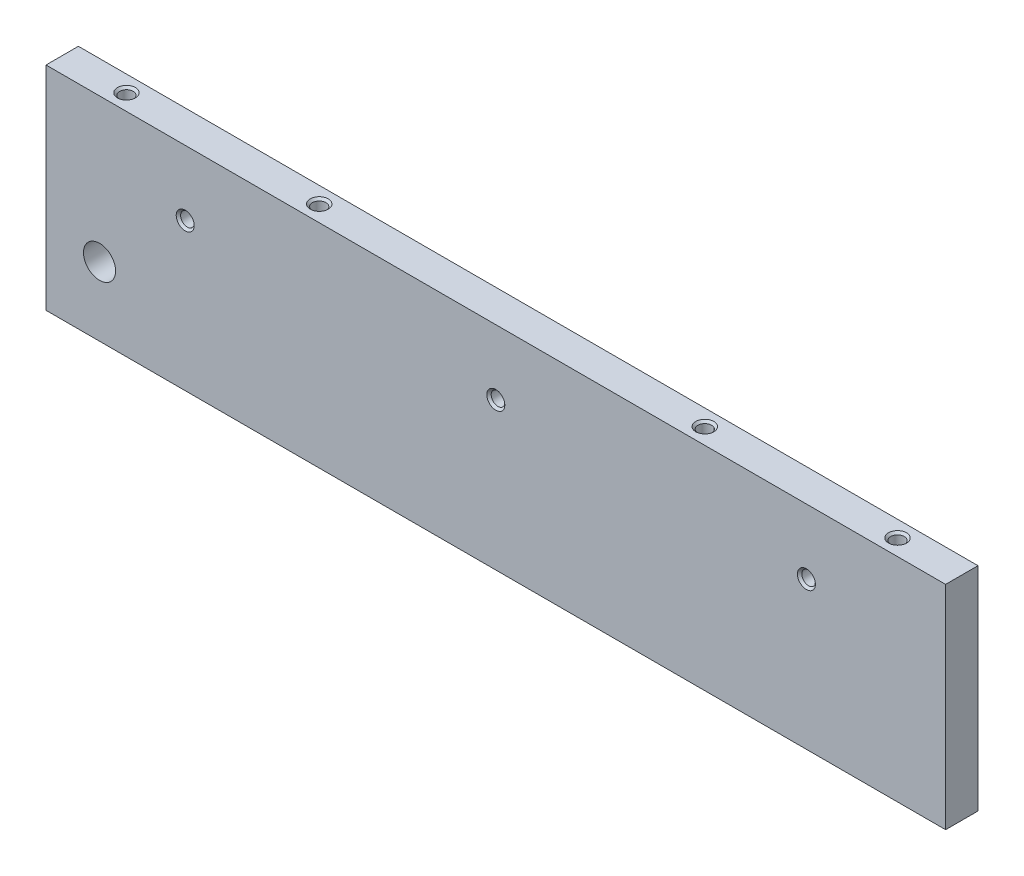
SolidWorks part; units mm, degrees
ref_plane "Front Plane" through (0, 0, 0) normal (0, 0, 1) x (1, 0, 0)
ref_plane "Top Plane" through (0, 0, 0) normal (0, 1, 0) x (1, 0, 0)
ref_plane "Right Plane" through (0, 0, 0) normal (1, 0, 0) x (0, 0, -1)
sketch "Sketch1" plane through (0, 0, 0) normal (0, 0, 1) x (1, 0, 0)
  line L1 (-133.35, 0) -> (133.35, 0)
  line L2 (-133.35, 0) -> (-133.35, -62.992)
  line L3 (-133.35, -62.992) -> (133.35, -62.992)
  line L4 (133.35, 0) -> (133.35, -62.992)
  dimension "D1" = 62.992
  dimension "D2" = 266.7
extrude "Boss-Extrude1" add sketch "Sketch1" along normal blind 9.6012
hole_wizard "#10-32 Tapped Hole1" positions "Sketch3" profile "Sketch2" tap size "#10-32" standard "ANSI Inch" end condition up to next
sketch "Sketch3" plane through (0, 0, 9.6012) normal (0, 0, 1) x (1, 0, 0)
  point P0 (92.075, -19.304)
  point P2 (0, -19.304)
  point P4 (-92.075, -19.304)
  dimension "D1" = 92.075
  dimension "D2" = 92.075
  dimension "D3" = 19.304
sketch "Sketch2" plane through (92.075, -19.304, 9.6012) normal (1, 0, 0) x (0, -1, 0)
  line L0 (0, 0) -> (0, 9.6012)
  line L1 (0, 9.6012) -> (2.667, 9.6012)
  line L2 (2.0193, 8.9535) -> (2.0193, 0.6477)
  line L3 (2.0193, 0.6477) -> (2.667, 0)
  line L5 (2.667, 0) -> (0, 0)
  line L6 (-2.0193, 0.6477) -> (-2.667, 0) construction
  line L7 (2.667, 9.6012) -> (2.0193, 8.9535)
  line L8 (-2.667, 9.6012) -> (-2.0193, 8.9535) construction
  line L11 (0, -6.35) -> (0, 107.95) construction
  dimension "Thread Major Dia." = 4.0386
  dimension "Thru Tap Drill Depth" = 9.6012
  dimension "Near C'Sink Dia." = 5.334
  dimension "Near C'Sink Angle" = 90
  dimension "Far C'Sink Dia." = 5.334
  dimension "Far C'Sink Angle" = 90
hole_wizard "3/8 (0.3750) Dowel Hole1" positions "Sketch5" profile "Sketch4" hole size "3/8" standard "ANSI Inch" end condition up to next
sketch "Sketch5" plane through (0, 0, 9.6012) normal (0, 0, 1) x (1, 0, 0)
  point P0 (-117.475, -42.5958)
  dimension "D1" = 42.5958
  dimension "D2" = 117.475
sketch "Sketch4" plane through (-117.475, -42.5958, 9.6012) normal (1, 0, 0) x (0, -1, 0)
  line L0 (0, 0) -> (0, 9.6012)
  line L1 (0, 9.6012) -> (4.7625, 9.6012)
  line L2 (4.7625, 9.6012) -> (4.7625, 0)
  line L5 (4.7625, 0) -> (0, 0)
  line L11 (0, -6.35) -> (0, 107.95) construction
  dimension "Thru Hole Dia." = 9.525
  dimension "Thru Hole Depth" = 9.6012
hole_wizard "#10-32 Tapped Hole2" positions "Sketch14" profile "Sketch13" tap size "#10-32" standard "ANSI Inch"
sketch "Sketch14" plane through (0, 0, 0) normal (0, 1, 0) x (1, 0, 0)
  point P0 (114.3, -4.8006)
  point P2 (57.15, -4.8006)
  point P4 (-57.15, -4.8006)
  point P6 (-114.3, -4.8006)
  dimension "D1" = 4.8006
  dimension "D2" = 57.15
  dimension "D3" = 57.15
  dimension "D4" = 57.15
  dimension "D5" = 57.15
sketch "Sketch13" plane through (114.3, 0, 4.8006) normal (1, 0, 0) x (0, 0, 1)
  line L0 (0, 0) -> (0, 20.2633)
  line L1 (0, 20.2633) -> (2.0193, 19.05)
  line L2 (2.0193, 19.05) -> (2.0193, 0.6477)
  line L3 (2.0193, 0.6477) -> (2.667, 0)
  line L5 (2.667, 0) -> (0, 0)
  line L6 (-2.0193, 0.6477) -> (-2.667, 0) construction
  line L10 (0, 20.2633) -> (-2.0193, 19.05) construction
  line L11 (0, -6.35) -> (0, 107.95) construction
  dimension "Tap Drill Dia." = 4.0386
  dimension "Tap Drill Depth" = 19.05
  dimension "Near C'Sink Dia." = 5.334
  dimension "Near C'Sink Angle" = 90
  dimension "Drill Angle" = 118
sketch "Sketch6" plane through (0, 0, 0) normal (0, 1, 0) x (1, 0, 0)
  line L1 (-133.35, 222.25) -> (133.35, 222.25)
  line L2 (-133.35, 222.25) -> (-133.35, -14.3002)
  line L3 (-133.35, -14.3002) -> (133.35, -14.3002)
  line L4 (133.35, 222.25) -> (133.35, -14.3002)
  point P4 (0, 222.25)
  dimension "D1" = 14.3002
  dimension "D2" = 266.7
  dimension "D3" = 222.25
extrude "Boss-Extrude2" [suppressed] add sketch "Sketch6" along normal blind 6.35 separate body
hole_wizard "1/2 (0.5000) Dowel Hole1" [suppressed] positions "Sketch8" profile "Sketch7" hole size "1/2" standard "ANSI Inch"
sketch "Sketch8" [suppressed] plane through (0, 6.35, 0) normal (0, 1, 0) x (1, 0, 0)
  point P0 (114.3, 201.6252)
  point P2 (-114.3, 201.6252)
  dimension "D1" = 201.6252
  dimension "D2" = 114.3
  dimension "D3" = 114.3
sketch "Sketch7" plane through (114.3, 6.35, -201.6252) normal (1, 0, 0) x (0, 0, 1)
  line L0 (0, 0) -> (0, 6.35)
  line L1 (0, 6.35) -> (6.35, 6.35)
  line L2 (6.35, 6.35) -> (6.35, 0)
  line L5 (6.35, 0) -> (0, 0)
  line L11 (0, -6.35) -> (0, 107.95) construction
  dimension "Thru Hole Dia." = 12.7
  dimension "Thru Hole Depth" = 6.35
hole_wizard "1/2 (0.5000) Dowel Hole2" [suppressed] positions "Sketch10" profile "Sketch9" hole size "1/2" standard "ANSI Inch"
sketch "Sketch10" [suppressed] plane through (0, 6.35, 0) normal (0, 1, 0) x (1, 0, 0)
  point P0 (76.2, 74.6125)
  point P2 (-76.2, 74.6125)
  dimension "D1" = 74.6125
  dimension "D2" = 76.2
  dimension "D3" = 76.2
sketch "Sketch9" plane through (76.2, 6.35, -74.6125) normal (1, 0, 0) x (0, 0, 1)
  line L0 (0, 0) -> (0, 6.35)
  line L1 (0, 6.35) -> (6.35, 6.35)
  line L2 (6.35, 6.35) -> (6.35, 0)
  line L5 (6.35, 0) -> (0, 0)
  line L11 (0, -6.35) -> (0, 107.95) construction
  dimension "Thru Hole Dia." = 12.7
  dimension "Thru Hole Depth" = 6.35
hole_wizard "#11 (0.191) Diameter Hole1" [suppressed] positions "Sketch12" profile "Sketch11" hole size "#11" standard "ANSI Inch"
sketch "Sketch12" [suppressed] plane through (0, 6.35, 0) normal (0, 1, 0) x (1, 0, 0)
  point P0 (114.3, -4.8006)
  point P2 (-114.3, -4.8006)
  point P4 (57.15, -4.8006)
  point P6 (-57.15, -4.8006)
  dimension "D1" = 57.15
  dimension "D2" = 57.15
  dimension "D3" = 57.15
  dimension "D4" = 57.15
  dimension "D5" = 4.8006
sketch "Sketch11" plane through (114.3, 6.35, 4.8006) normal (1, 0, 0) x (0, 0, 1)
  line L0 (0, 0) -> (0, 6.35)
  line L1 (0, 6.35) -> (2.4257, 6.35)
  line L2 (2.4257, 6.35) -> (2.4257, 0)
  line L5 (2.4257, 0) -> (0, 0)
  line L11 (0, -6.35) -> (0, 107.95) construction
  dimension "Thru Hole Dia." = 4.8514
  dimension "Thru Hole Depth" = 6.35
